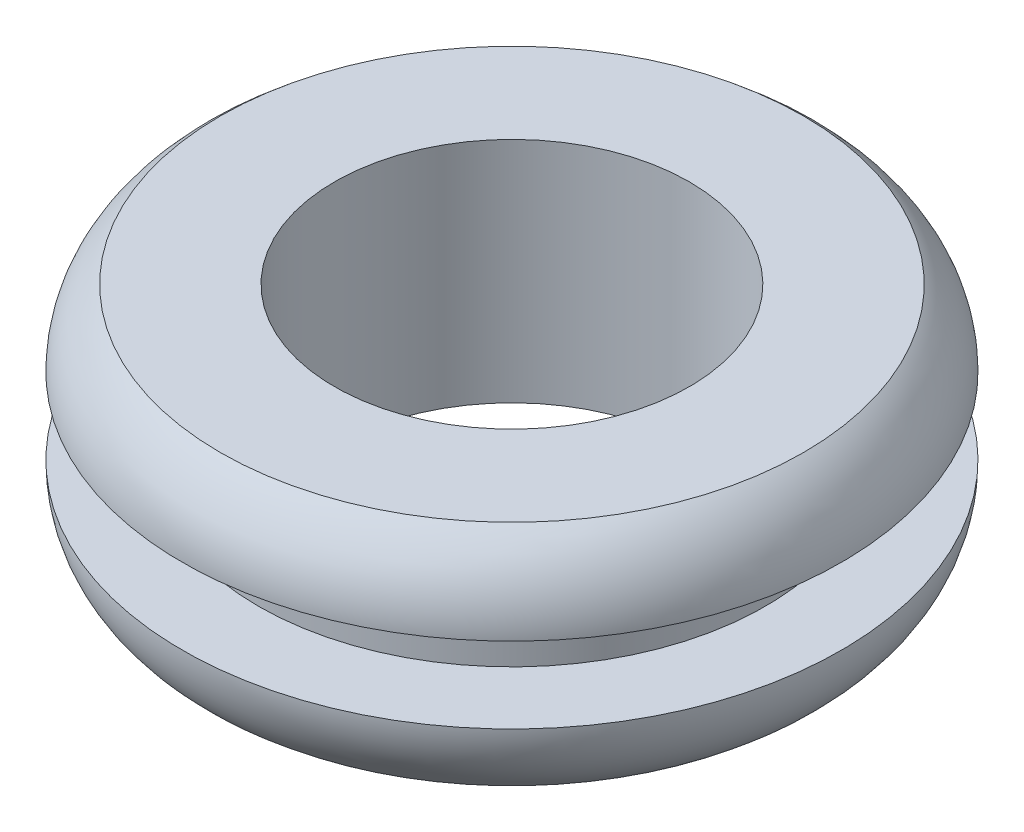
SolidWorks part; units mm, degrees
material "Rubber"
ref_plane "Front Plane" through (0, 0, 0) normal (0, 0, 1) x (1, 0, 0)
ref_plane "Top Plane" through (0, 0, 0) normal (0, 1, 0) x (1, 0, 0)
ref_plane "Right Plane" through (0, 0, 0) normal (1, 0, 0) x (0, 0, -1)
sketch "Sketch1" plane through (0, 0, 0) normal (1, 0, 0) x (0, 0, -1)
  line L0 (-15.875, 7.1438) -> (15.875, 7.1438) construction
  line L1 (20.6375, -7.1437) -> (-20.6375, -7.1438) construction
  line L2 (20.6375, -7.1437) -> (20.6375, 7.1437) construction
  line L3 (20.6375, 7.1437) -> (-20.6375, 7.1438) construction
  line L4 (-20.6375, -7.1438) -> (-20.6375, 7.1438) construction
  line L5 (20.6375, -7.1437) -> (-20.6375, 7.1438) construction
  line L6 (20.6375, 7.1437) -> (-20.6375, -7.1438) construction
  line L7 (-11.1125, -7.1437) -> (11.1125, -7.1437) construction
  line L8 (-20.6375, -2.3813) -> (-20.6375, 2.3812) construction
  point P0 (0, 0)
  point P9 (0, 7.1438)
  point P12 (0, -7.1438)
  point P15 (-20.6375, 0)
  dimension "Overall Height" = 14.2875
  dimension "Flange Diameter" = 41.275
  dimension "For Hole Diameter" = 31.75
  dimension "ID" = 22.225
  dimension "For Material Thickness" = 4.7625
sketch "Sketch2" plane through (0, 0, 0) normal (1, 0, 0) x (0, 0, -1)
  line L1 (20.6375, -7.1437) -> (-20.6375, -7.1437) construction
  line L3 (-20.6375, 0) -> (-15.875, 0) construction
  line L6 (-20.6375, -7.1438) -> (-20.6375, 7.1438) construction
  line L12 (0, -7.1438) -> (0, 7.1438) construction
  line L15 (-11.1125, -7.1437) -> (-11.1125, 7.1437)
  line L17 (-15.875, 7.1438) -> (15.875, 7.1438) construction
  line L18 (-11.1125, 7.1437) -> (-18.2563, 7.1438)
  line L20 (-20.6375, 2.3812) -> (-15.875, 2.3812)
  line L21 (-15.875, 2.3812) -> (-15.875, -2.3813)
  line L22 (-15.875, -2.3813) -> (-20.6375, -2.3813)
  line L23 (-11.1125, -7.1437) -> (-18.2563, -7.1438)
  arc A8 (-20.6375, 2.3812) -> (-18.2563, 7.1438) centre (-14.6844, 2.3813) cw
  arc A9 (-20.6375, -2.3813) -> (-18.2563, -7.1438) centre (-14.6844, -2.3813) ccw
  point P4 (0, 0)
  point P11 (-18.2563, 0)
revolve "Revolve1" add sketch "Sketch2" angle 360 about L12
